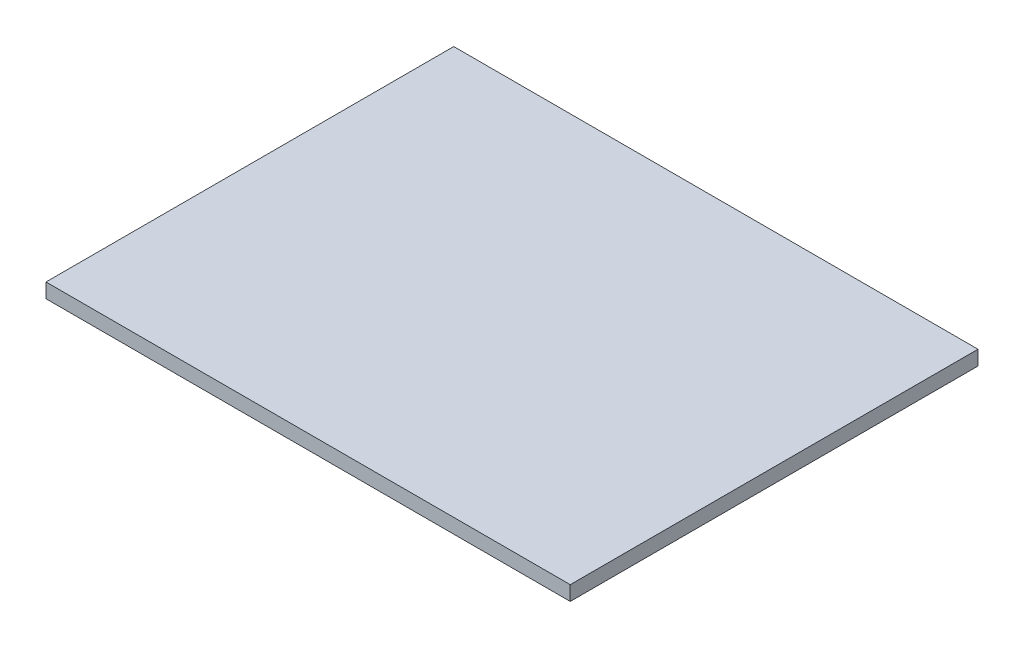
SolidWorks part; units mm, degrees
ref_plane "Ön Düzlem" through (0, 0, 0) normal (0, 0, 1) x (1, 0, 0)
ref_plane "Üst Düzlem" through (0, 0, 0) normal (0, 1, 0) x (1, 0, 0)
ref_plane "Sağ Düzlem" through (0, 0, 0) normal (1, 0, 0) x (0, 0, -1)
sketch "Çizim1" plane through (0, 0, 0) normal (0, 1, 0) x (1, 0, 0)
  line L1 (-90, -70) -> (90, -70)
  line L2 (-90, -70) -> (-90, 70)
  line L3 (-90, 70) -> (90, 70)
  line L4 (90, -70) -> (90, 70)
  line L5 (0, 70) -> (0, -70) construction
  line L6 (-90, 0) -> (90, 0) construction
  point P0 (0, 0)
  dimension "D1" = 180
  dimension "D2" = 140
extrude "Yükseklik-Ekstrüzyon1" add sketch "Çizim1" along normal blind 5
